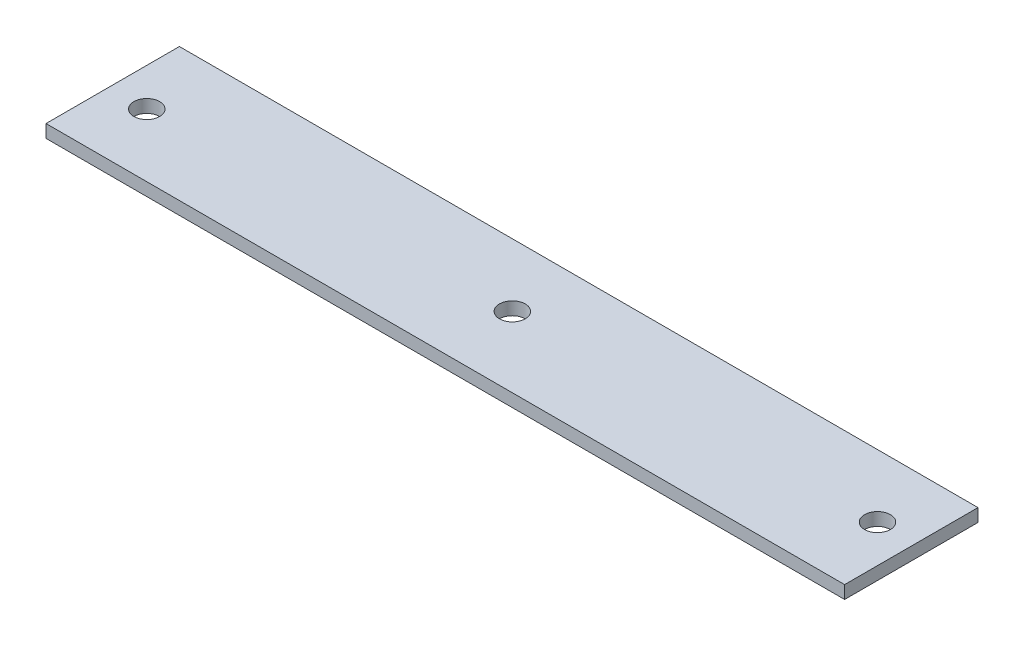
SolidWorks part; units mm, degrees
ref_plane "Front Plane" through (0, 0, 0) normal (0, 0, 1) x (1, 0, 0)
ref_plane "Top Plane" through (0, 0, 0) normal (0, 1, 0) x (1, 0, 0)
ref_plane "Right Plane" through (0, 0, 0) normal (1, 0, 0) x (0, 0, -1)
sketch "Sketch1" plane through (0, 0, 0) normal (0, 1, 0) x (1, 0, 0)
  line L0 (-46.068, 8.0295) -> (46.732, 8.0295)
  line L1 (-46.068, 8.0295) -> (-46.068, -7.4705)
  line L2 (-46.068, -7.4705) -> (46.732, -7.4705)
  line L3 (46.732, 8.0295) -> (46.732, -7.4705)
  circle A0 centre (-41.668, -0.1605) radius 1.5
  circle A1 centre (-0.068, 0.7195) radius 1.5
  circle A2 centre (42.352, 0.7295) radius 1.5
  dimension "D5" = 3
  dimension "D8" = 3
  dimension "D11" = 3
  dimension "D1" = 15.5
  dimension "D2" = 92.8
  dimension "D3" = 7.31
  dimension "D4" = 4.4
  dimension "D6" = 46
  dimension "D7" = 8.19
  dimension "D9" = 88.42
  dimension "D10" = 8.2
extrude "Boss-Extrude1" add sketch "Sketch1" along normal blind 1.5
